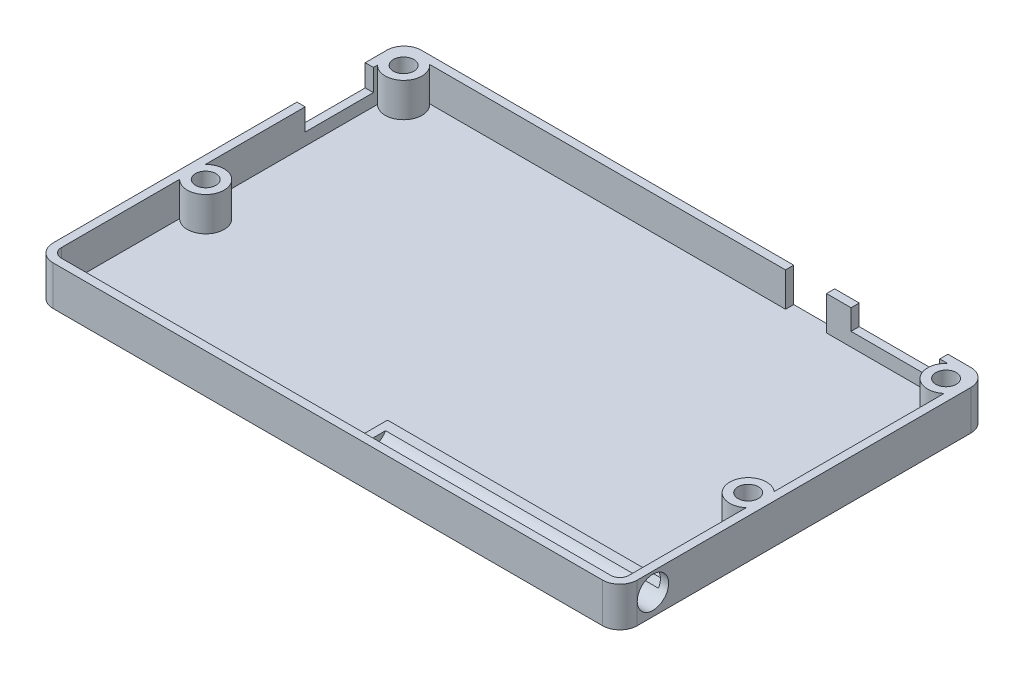
SolidWorks part; units mm, degrees
ref_plane "Front Plane" through (0, 0, 0) normal (0, 0, 1) x (1, 0, 0)
ref_plane "Top Plane" through (0, 0, 0) normal (0, 1, 0) x (1, 0, 0)
ref_plane "Right Plane" through (0, 0, 0) normal (1, 0, 0) x (0, 0, -1)
sketch "Sketch1" plane through (0, 0, 0) normal (0, 1, 0) x (1, 0, 0)
  line L0 (62.865, 49.276) -> (62.865, 98.171)
  line L1 (65.405, 100.711) -> (145.923, 100.711)
  line L2 (148.463, 49.276) -> (148.463, 98.171)
  line L3 (65.405, 46.736) -> (145.923, 46.736)
  arc A0 (65.405, 100.711) -> (62.865, 98.171) centre (65.405, 98.171) ccw
  arc A1 (148.463, 98.171) -> (145.923, 100.711) centre (145.923, 98.171) ccw
  arc A2 (145.923, 46.736) -> (148.463, 49.276) centre (145.923, 49.276) ccw
  arc A3 (62.865, 49.276) -> (65.405, 46.736) centre (65.405, 49.276) ccw
extrude "Boss-Extrude1" add sketch "Sketch1" along normal blind 0.8
sketch "Sketch3" plane through (0, 0.8, 0) normal (0, 1, 0) x (1, 0, 0)
  line L0 (65.405, 46.736) -> (145.923, 46.736) construction
  line L1 (148.463, 49.276) -> (148.463, 98.171) construction
  line L2 (145.923, 100.711) -> (65.405, 100.711) construction
  line L3 (62.865, 98.171) -> (62.865, 49.276) construction
  line L4 (65.405, 46.736) -> (145.923, 46.736)
  line L5 (148.463, 49.276) -> (148.463, 98.171)
  line L6 (145.923, 100.711) -> (65.405, 100.711)
  line L7 (62.865, 98.171) -> (62.865, 49.276)
  line L8 (64.065, 98.171) -> (64.065, 49.276)
  line L9 (65.405, 47.936) -> (145.923, 47.936)
  line L10 (147.263, 49.276) -> (147.263, 98.171)
  line L11 (145.923, 99.511) -> (65.405, 99.511)
  arc A0 (145.923, 46.736) -> (148.463, 49.276) centre (145.923, 49.276) ccw construction
  arc A1 (148.463, 98.171) -> (145.923, 100.711) centre (145.923, 98.171) ccw construction
  arc A2 (65.405, 100.711) -> (62.865, 98.171) centre (65.405, 98.171) ccw construction
  arc A3 (62.865, 49.276) -> (65.405, 46.736) centre (65.405, 49.276) ccw construction
  arc A4 (145.923, 46.736) -> (148.463, 49.276) centre (145.923, 49.276) ccw
  arc A5 (148.463, 98.171) -> (145.923, 100.711) centre (145.923, 98.171) ccw
  arc A6 (65.405, 100.711) -> (62.865, 98.171) centre (65.405, 98.171) ccw
  arc A7 (62.865, 49.276) -> (65.405, 46.736) centre (65.405, 49.276) ccw
  arc A8 (64.065, 49.276) -> (65.405, 47.936) centre (65.405, 49.276) ccw
  arc A9 (145.923, 47.936) -> (147.263, 49.276) centre (145.923, 49.276) ccw
  arc A10 (147.263, 98.171) -> (145.923, 99.511) centre (145.923, 98.171) ccw
  arc A11 (65.405, 99.511) -> (64.065, 98.171) centre (65.405, 98.171) ccw
  dimension "D1" = 1.2
extrude "Boss-Extrude2" add sketch "Sketch3" along normal blind 5
sketch "Sketch4" plane through (62.865, 0, 0) normal (-1, 0, 0) x (0, 0, 1)
  line L0 (-98.171, 5.8) -> (-49.276, 5.8) construction
  line L1 (-95.011, 5.8) -> (-85.011, 5.8)
  line L2 (-95.011, 5.8) -> (-95.011, 2.6)
  line L3 (-95.011, 2.6) -> (-85.011, 2.6)
  line L4 (-85.011, 5.8) -> (-85.011, 2.6)
  line L5 (-100.711, 5.8) -> (-100.711, 0) construction
  dimension "D1" = 3.2
  dimension "D2" = 10
  dimension "D3" = 5.7
extrude "Cut-Extrude1" cut sketch "Sketch4" against normal blind 1.2
sketch "Sketch6" plane through (0, 0, -100.711) normal (0, 0, -1) x (-1, 0, 0)
  line L0 (-145.923, 5.8) -> (-65.405, 5.8) construction
  line L1 (-125.963, 5.8) -> (-119.963, 5.8)
  line L2 (-125.963, 5.8) -> (-125.963, 0.8)
  line L3 (-125.963, 0.8) -> (-119.963, 0.8)
  line L4 (-119.963, 5.8) -> (-119.963, 0.8)
  line L5 (-148.463, 5.8) -> (-148.463, 0) construction
  dimension "D1" = 6
  dimension "D2" = 5
  dimension "D3" = 28.5
extrude "Cut-Extrude2" cut sketch "Sketch6" against normal blind 1.2
sketch "Sketch7" plane through (0, 0, -100.711) normal (0, 0, -1) x (-1, 0, 0)
  line L0 (-145.923, 5.8) -> (-125.963, 5.8) construction
  line L1 (-142.563, 5.8) -> (-129.563, 5.8)
  line L2 (-142.563, 5.8) -> (-142.563, 2.8)
  line L3 (-142.563, 2.8) -> (-129.563, 2.8)
  line L4 (-129.563, 5.8) -> (-129.563, 2.8)
  line L5 (-148.463, 5.8) -> (-148.463, 0) construction
  point P6 (-136.063, 2.8)
  dimension "D1" = 13
  dimension "D2" = 3
  dimension "D3" = 12.4
extrude "Cut-Extrude3" cut sketch "Sketch7" against normal blind 1.2
sketch "Sketch8" plane through (0, 0.8, 0) normal (0, 1, 0) x (1, 0, 0)
  line L0 (62.865, 98.171) -> (62.865, 95.011) construction
  line L1 (119.963, 100.711) -> (65.405, 100.711) construction
  circle A0 centre (66.015, 97.486) radius 1.5
  circle A1 centre (66.015, 97.486) radius 2.7
  dimension "D3" = 3
  dimension "D1" = 3.15
  dimension "D2" = 3.225
  dimension "D4" = 1.2
extrude "Boss-Extrude4" add sketch "Sketch8" along normal blind 5
sketch "Sketch9" plane through (0, 0.8, 0) normal (0, 1, 0) x (1, 0, 0)
  circle A0 centre (145.5, 97.5) radius 1.2 construction
  circle A1 centre (145.5, 97.5) radius 1.2 construction
  circle A2 centre (145.5, 97.5) radius 1.5
  circle A3 centre (145.5, 97.5) radius 2.7
  dimension "D1" = 3
  dimension "D2" = 1.2
extrude "Boss-Extrude5" add sketch "Sketch9" along normal blind 5
sketch "Sketch10" plane through (0, 0.8, 0) normal (0, 1, 0) x (1, 0, 0)
  circle A0 centre (66, 68.5) radius 1.2 construction
  circle A1 centre (66, 68.5) radius 1.2 construction
  circle A2 centre (66, 68.5) radius 1.5
  circle A3 centre (66, 68.5) radius 2.7
  dimension "D1" = 3
  dimension "D2" = 1.2
extrude "Boss-Extrude6" add sketch "Sketch10" along normal blind 5
sketch "Sketch11" plane through (0, 0.8, 0) normal (0, 1, 0) x (1, 0, 0)
  circle A0 centre (145.5, 68.5) radius 1.2 construction
  circle A1 centre (145.5, 68.5) radius 1.2 construction
  circle A2 centre (145.5, 68.5) radius 1.5
  circle A3 centre (145.5, 68.5) radius 2.7
  dimension "D1" = 3
  dimension "D2" = 1.2
extrude "Boss-Extrude7" add sketch "Sketch11" along normal blind 5
sketch "Sketch13" plane through (148.463, 0, 0) normal (1, 0, 0) x (0, 0, -1)
  line L0 (49.276, 5.8) -> (49.276, 0) construction
  line L1 (49.276, 0) -> (98.171, 0) construction
  circle A0 centre (51.576, 3.1) radius 2.3
  dimension "D1" = 4.6
  dimension "D2" = 3.1
extrude "Cut-Extrude8" cut sketch "Sketch13" against normal blind 5
sketch "Sketch15" plane through (0, 0.8, 0) normal (0, 1, 0) x (1, 0, 0)
  line L0 (147.263, 51.576) -> (147.263, 66.455) construction
  line L1 (147.263, 55.076) -> (106.063, 55.076)
  line L2 (147.263, 55.076) -> (147.263, 47.936)
  line L3 (147.263, 47.936) -> (106.063, 47.936)
  line L4 (106.063, 55.076) -> (106.063, 47.936)
  line L5 (65.405, 47.936) -> (145.923, 47.936) construction
  dimension "D1" = 41.2
  dimension "D2" = 1.2
extrude "Boss-Extrude9" add sketch "Sketch15" along normal blind 1.2
sketch "Sketch16" plane through (147.263, 0, 0) normal (1, 0, 0) x (0, 0, -1)
  circle A0 centre (51.576, 3.1) radius 2.3 construction
  circle A1 centre (51.576, 3.1) radius 2.3
extrude "Cut-Extrude9" cut sketch "Sketch16" against normal blind 40
